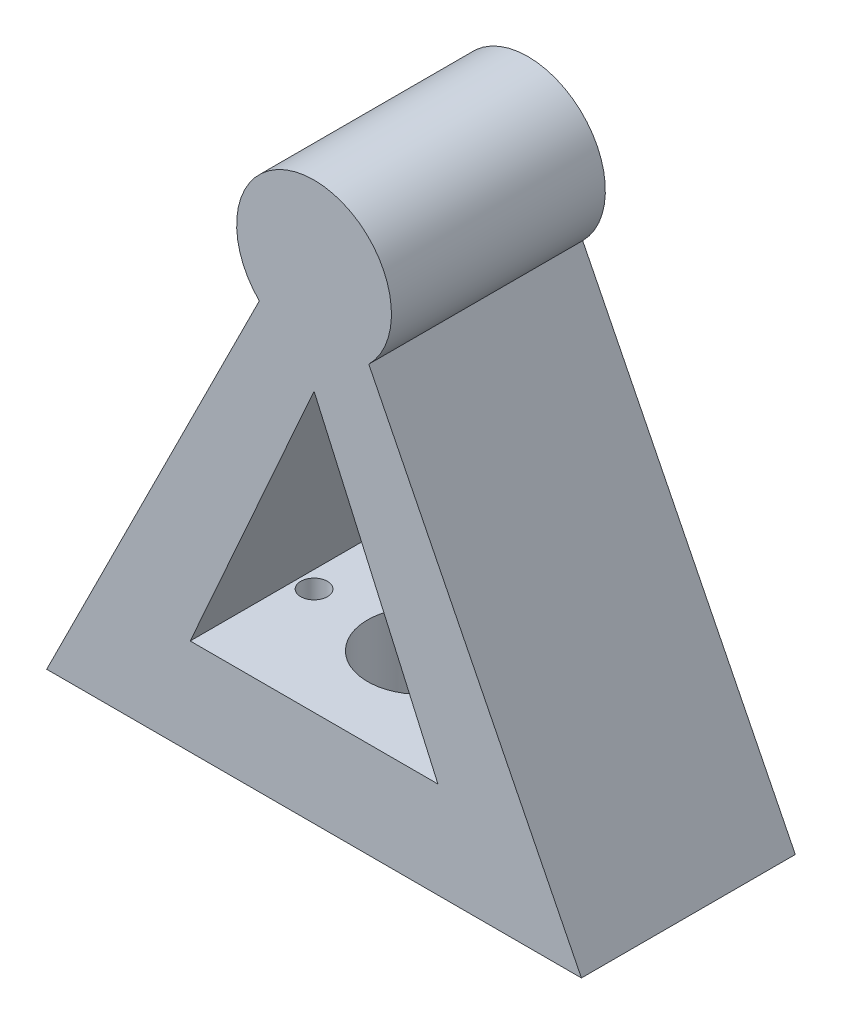
SolidWorks part; units mm, degrees
ref_plane "Alzado" through (0, 0, 0) normal (0, 0, 1) x (1, 0, 0)
ref_plane "Planta" through (0, 0, 0) normal (0, 1, 0) x (1, 0, 0)
ref_plane "Vista lateral" through (0, 0, 0) normal (1, 0, 0) x (0, 0, -1)
sketch "Croquis1" plane through (0, 0, 0) normal (0, 0, 1) x (1, 0, 0)
  line L0 (-12.1049, -39.7647) -> (7.7775, 0)
  line L3 (-12.1049, -39.7647) -> (37.8951, -39.7647)
  line L5 (18.0128, 0) -> (37.8951, -39.7647)
  line L9 (1.3144, -30.7647) -> (12.8951, -4.7463)
  line L10 (12.8951, -4.7463) -> (24.4758, -30.7647)
  line L11 (14.6296, -30.7647) -> (1.3144, -30.7647)
  line L12 (14.6296, -30.7647) -> (24.4758, -30.7647)
  arc A0 (7.7775, 0) -> (18.0128, 0) centre (12.8951, 5.1177) cw
  dimension "D1" = 50
extrude "Saliente-Extruir1" add sketch "Croquis1" along normal blind 20
sketch "Croquis4" plane through (0, -39.7647, 0) normal (0, -1, 0) x (1, 0, 0)
  circle A0 centre (12.8951, 10) radius 5
  circle A1 centre (22.8951, 10) radius 1.25
  circle A2 centre (2.8951, 10) radius 1.25
  dimension "D1" = 10
  dimension "D2" = 2.5
  dimension "D4" = 2.5
  dimension "D3" = 10
extrude "Cortar-Extruir3" cut sketch "Croquis4" against normal blind 9
